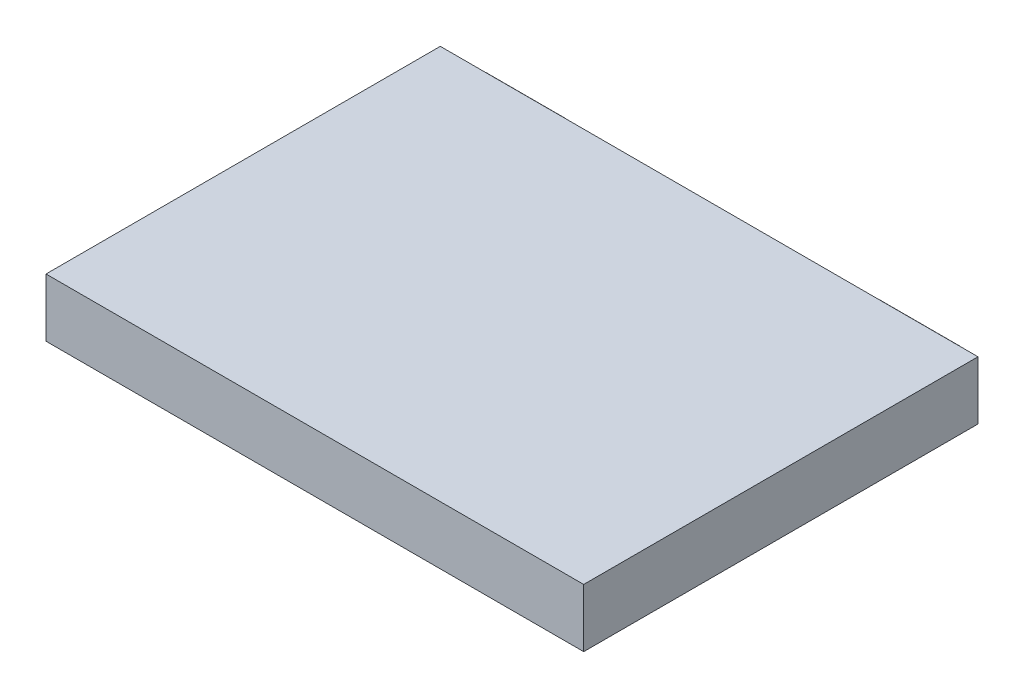
SolidWorks part; units mm, degrees
ref_plane "前视基准面" through (0, 0, 0) normal (0, 0, 1) x (1, 0, 0)
ref_plane "上视基准面" through (0, 0, 0) normal (0, 1, 0) x (1, 0, 0)
ref_plane "右视基准面" through (0, 0, 0) normal (1, 0, 0) x (0, 0, -1)
sketch "Sketch1" plane through (0, 0, 0) normal (0, 1, 0) x (1, 0, 0)
  line L1 (-60, 44) -> (60, 44)
  line L2 (-60, 44) -> (-60, -44)
  line L3 (-60, -44) -> (60, -44)
  line L4 (60, 44) -> (60, -44)
  line L5 (-60, 44) -> (60, -44) construction
  line L6 (-60, -44) -> (60, 44) construction
  point P0 (0, 0)
  dimension "D1" = 120
  dimension "D2" = 88
extrude "Boss-Extrude1" add sketch "Sketch1" along normal blind 13
sketch "Sketch2" plane through (0, 0, -44) normal (0, 0, -1) x (-1, 0, 0)
  line L0 (0, 0) -> (0, 13)
  line L1 (-52.8769, 10.0368) -> (-35.1231, 10.0368)
  line L2 (-52.8769, 10.0368) -> (-52.8769, 3.9632)
  line L3 (-52.8769, 3.9632) -> (-35.1231, 3.9632)
  line L4 (-35.1231, 10.0368) -> (-35.1231, 3.9632)
  line L5 (-52.8769, 10.0368) -> (-35.1231, 3.9632) construction
  line L6 (-52.8769, 3.9632) -> (-35.1231, 10.0368) construction
  line L7 (-60, 13) -> (60, 13) construction
  line L8 (52.8769, 3.9632) -> (35.1231, 10.0368) construction
  line L9 (52.8769, 10.0368) -> (35.1231, 3.9632) construction
  line L10 (35.1231, 10.0368) -> (35.1231, 3.9632)
  line L11 (52.8769, 3.9632) -> (35.1231, 3.9632)
  line L12 (52.8769, 10.0368) -> (52.8769, 3.9632)
  line L13 (52.8769, 10.0368) -> (35.1231, 10.0368)
  point P0 (-44, 7)
  point P14 (44, 7)
extrude "Boss-Extrude2" add sketch "Sketch2" along normal blind 3 contours L4 L1 L2 L3 | L12 L13 L10 L11
